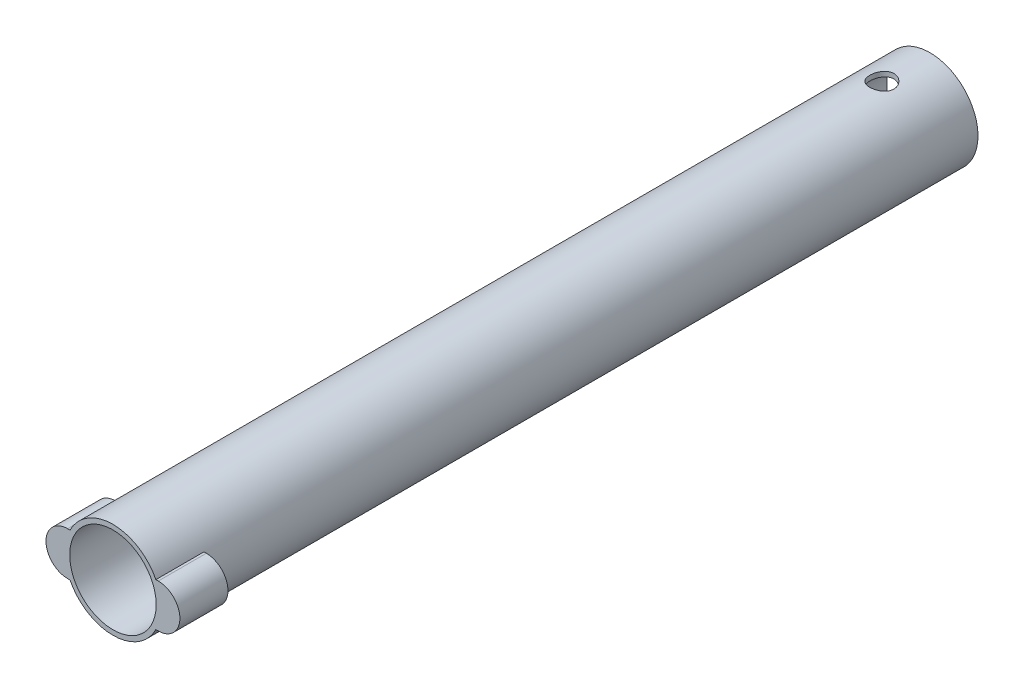
SolidWorks part; units mm, degrees
ref_plane "Front Plane" through (0, 0, 0) normal (0, 0, 1) x (1, 0, 0)
ref_plane "Top Plane" through (0, 0, 0) normal (0, 1, 0) x (1, 0, 0)
ref_plane "Right Plane" through (0, 0, 0) normal (1, 0, 0) x (0, 0, -1)
sketch "Sketch1" plane through (0, 0, 0) normal (0, 0, 1) x (1, 0, 0)
  circle A0 centre (0, 0) radius 10
  circle A1 centre (0, 0) radius 9
  dimension "D1" = 20
  dimension "D2" = 18
extrude "Boss-Extrude1" add sketch "Sketch1" along normal blind 170
sketch "Sketch2" plane through (0, 0, 170) normal (0, 0, 1) x (1, 0, 0)
  line L0 (-9.4303, 0) -> (10.5697, 0) construction
  line L1 (-9.4303, 4.5) -> (-8.9303, 4.5)
  line L2 (-9.4303, -4.5) -> (-8.9303, -4.5)
  line L3 (8.9303, 4.5) -> (9.4303, 4.5)
  line L4 (8.9303, -4.5) -> (9.4303, -4.5)
  arc A0 (-9.4303, 4.5) -> (-9.4303, -4.5) centre (-9.4303, 0) ccw
  circle A2 centre (0, 0) radius 10 construction
  arc A3 (-8.9303, 4.5) -> (-8.9303, -4.5) centre (0, 0) ccw
  arc A4 (8.9303, -4.5) -> (8.9303, 4.5) centre (0, 0) ccw
  arc A6 (9.4303, 4.5) -> (9.4303, -4.5) centre (9.4303, 0) cw
  point P2 (0, 0)
  dimension "D6" = 0.5
  dimension "D1" = 20
  dimension "D2" = 9
  dimension "D3" = 0.5
  dimension "D4" = 0.5
  dimension "D5" = 0.5
extrude "Boss-Extrude2" add sketch "Sketch2" against normal blind 10
sketch "Sketch3" plane through (0, 0, 0) normal (0, 1, 0) x (1, 0, 0)
  circle A0 centre (0, -10) radius 2.5
  dimension "D1" = 5
  dimension "D2" = 10
extrude "Cut-Extrude1" cut sketch "Sketch3" against normal through all both and the other way through all
